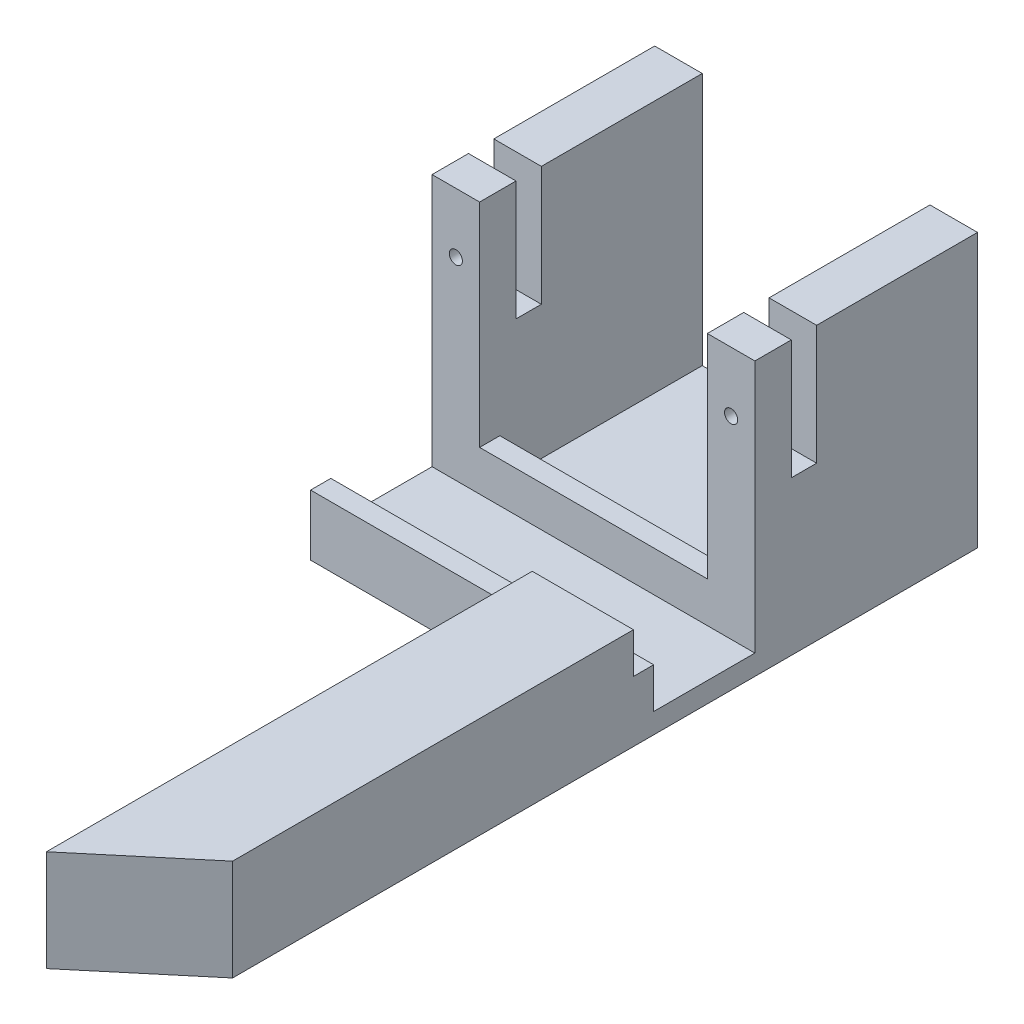
SolidWorks part; units mm, degrees
ref_plane "Front Plane" through (0, 0, 0) normal (0, 0, 1) x (1, 0, 0)
ref_plane "Top Plane" through (0, 0, 0) normal (0, 1, 0) x (1, 0, 0)
ref_plane "Right Plane" through (0, 0, 0) normal (1, 0, 0) x (0, 0, -1)
sketch "Sketch1" plane through (0, 0, 0) normal (0, 1, 0) x (1, 0, 0)
  line L1 (-15.95, 17) -> (15.95, 17)
  line L2 (-15.95, 17) -> (-15.95, -17)
  line L3 (-15.95, -17) -> (15.95, -17)
  line L4 (15.95, 17) -> (15.95, -17)
  line L5 (-15.95, 17) -> (15.95, -17) construction
  line L6 (-15.95, -17) -> (15.95, 17) construction
  point P0 (0, 0)
  dimension "D1" = 31.9
  dimension "D2" = 34
extrude "Boss-Extrude3" add sketch "Sketch1" along normal blind 2
sketch "Sketch2" plane through (0, 2, 0) normal (0, 1, 0) x (1, 0, 0)
  line L0 (0, 17) -> (0, -17) construction
  line L1 (-15.95, 17) -> (15.95, 17)
  line L2 (-15.95, 17) -> (-15.95, -17)
  line L3 (-15.95, -17) -> (15.95, -17)
  line L4 (15.95, 17) -> (15.95, -17)
  line L5 (-15.95, 17) -> (-11.25, 17)
  line L6 (-15.95, 17) -> (-15.95, -5)
  line L7 (-15.95, -5) -> (-11.25, -5)
  line L8 (-11.25, 17) -> (-11.25, -5)
  line L9 (15.95, -5) -> (11.25, -5)
  line L10 (11.25, 17) -> (11.25, -5)
  line L11 (15.95, 17) -> (11.25, 17)
  line L12 (15.95, 17) -> (15.95, -5)
  point P14 (0, 0)
  dimension "D1" = 4.7
  dimension "D2" = 22
  dimension "D3" = 22
  dimension "D5" = 4.7
extrude "Boss-Extrude4" add sketch "Sketch2" along normal blind 25 contours L6 L5 L8 L7 | L12 L9 L10 L11
sketch "Sketch3" plane through (0, 2, 0) normal (0, 1, 0) x (1, 0, 0)
  line L1 (-11.25, -5) -> (11.25, -5)
  line L2 (-11.25, -5) -> (-11.25, -3)
  line L3 (-11.25, -3) -> (11.25, -3)
  line L4 (11.25, -5) -> (11.25, -3)
  line L5 (-15.95, -17) -> (15.95, -17)
  line L6 (-15.95, -17) -> (-15.95, -15)
  line L7 (-15.95, -15) -> (15.95, -15)
  line L8 (15.95, -17) -> (15.95, -15)
  dimension "D1" = 22.5
  dimension "D2" = 2
  dimension "D3" = 2
  dimension "D4" = 31.9
extrude "Boss-Extrude5" add sketch "Sketch3" along normal blind 4
sketch "Sketch6" plane through (0, 27, 0) normal (0, 1, 0) x (1, 0, 0)
  line L0 (15.95, 17) -> (15.95, -5) construction
  line L1 (-15.95, 17) -> (15.95, 17)
  line L2 (-15.95, 17) -> (-15.95, -1.4)
  line L3 (-15.95, -1.4) -> (15.95, -1.4)
  line L4 (15.95, 17) -> (15.95, -1.4)
  line L6 (-15.95, -1.4) -> (15.95, -1.4)
  line L7 (-15.95, -1.4) -> (-15.95, 1.1)
  line L8 (-15.95, 1.1) -> (15.95, 1.1)
  line L9 (15.95, -1.4) -> (15.95, 1.1)
  line M10 (-11.25, -5) -> (-11.25, 17)
  dimension "D1" = 18.4
  dimension "D2" = 2.5
  dimension "D3" = 31.9
extrude "Cut-Extrude1" cut sketch "Sketch6" against normal blind 11.8 contours L8 L3 L4 M10 | L8 L2 L3 M10
sketch "Sketch7" plane through (0, 0, 5) normal (0, 0, 1) x (1, 0, 0)
  line L1 (-15.95, 27) -> (-11.25, 27) construction
  line L2 (-15.95, 27) -> (-15.95, 2) construction
  line L3 (15.95, 27) -> (11.25, 27) construction
  line L4 (11.25, 27) -> (11.25, 6) construction
  circle A0 centre (-13.6, 21.1) radius 0.65
  circle A1 centre (13.6, 21.1) radius 0.65
  point P22 (-13.6, 21.1)
  point P23 (13.6, 21.1)
  dimension "D3" = 1.3
  dimension "D4" = 1.3
  dimension "D1" = 5.9
  dimension "D2" = 2.35
  dimension "D5" = 5.9
  dimension "D6" = 2.35
extrude "Cut-Extrude2" cut sketch "Sketch7" against normal blind 4
sketch "Sketch8" plane through (0, 0, 0) normal (0, 1, 0) x (1, 0, 0)
  line L0 (5.95, -65) -> (15.95, -56.609)
  line L1 (15.95, -17) -> (5.95, -17)
  line L2 (15.95, -17) -> (15.95, -56.609)
  line L4 (5.95, -17) -> (5.95, -65)
  dimension "D1" = 60
extrude "Boss-Extrude6" add sketch "Sketch8" along normal blind 10 contours L2 L0 L4 L1
